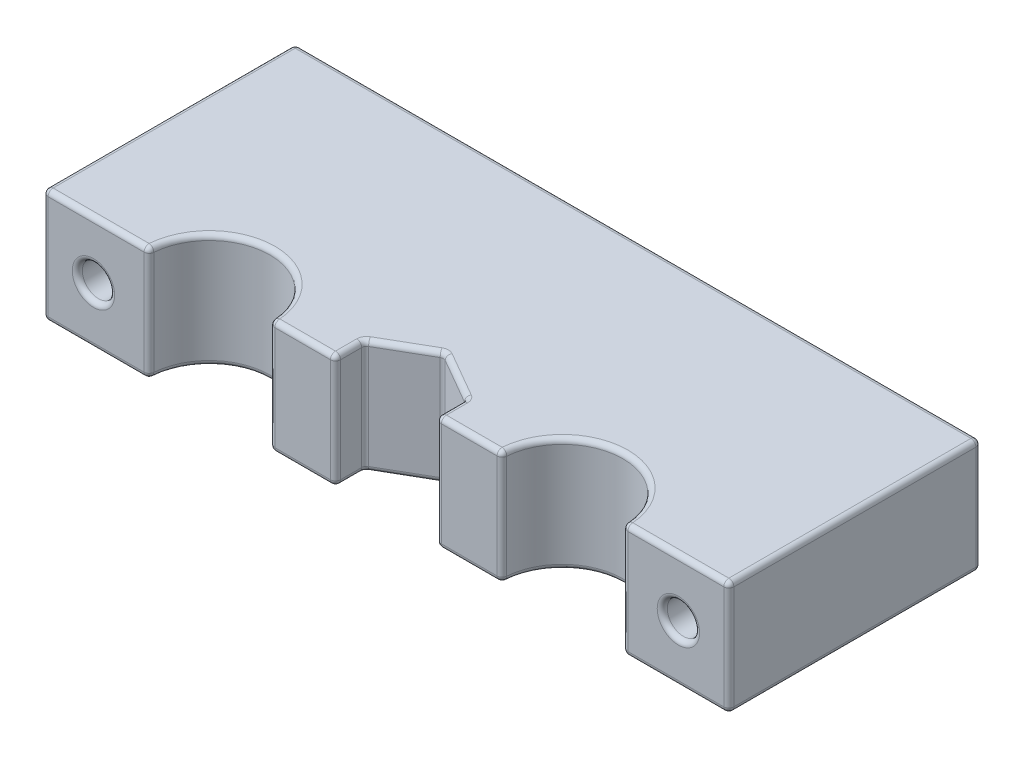
SolidWorks part; units mm, degrees
ref_plane "Front Plane" through (0, 0, 0) normal (0, 0, 1) x (1, 0, 0)
ref_plane "Top Plane" through (0, 0, 0) normal (0, 1, 0) x (1, 0, 0)
ref_plane "Right Plane" through (0, 0, 0) normal (1, 0, 0) x (0, 0, -1)
sketch "Sketch1" plane through (0, 0, 0) normal (0, 1, 0) x (1, 0, 0)
  line L0 (34, 0) -> (34, 25) construction
  line L5 (0, 0) -> (68, 0) construction
  line L6 (0, 0) -> (0, 25) construction
  line L13 (0, 25) -> (68, 25) construction
  line L14 (68, 0) -> (68, 25) construction
  line L15 (57.5, 0) -> (68, 0)
  line L16 (29, 2.8868) -> (29, -2.8868) construction
  line L17 (29, -2.8868) -> (34, -5.7735) construction
  line L18 (34, -5.7735) -> (39, -2.8868) construction
  line L19 (39, -2.8868) -> (39, 2.8868) construction
  line L20 (39, 2.8868) -> (34, 5.7735) construction
  line L21 (34, 5.7735) -> (29, 2.8868) construction
  line L22 (68, 0) -> (68, 25)
  line L23 (68, 25) -> (0, 25)
  line L24 (0, 25) -> (0, 0)
  line L25 (0, 0) -> (10.5, 0)
  line L26 (22.5, 0) -> (29, 0)
  line L27 (29, 0) -> (29, 2.8868)
  line L28 (29, 2.8868) -> (34, 5.7735)
  line L29 (34, 5.7735) -> (39, 2.8868)
  line L30 (39, 2.8868) -> (39, 0)
  line L31 (39, 0) -> (45.5, 0)
  circle A2 centre (16.5, 0) radius 6 construction
  circle A3 centre (34, 0) radius 5 construction
  circle A4 centre (51.5, 0) radius 6 construction
  arc A5 (10.5, 0) -> (22.5, 0) centre (16.5, 0) cw
  arc A6 (45.5, 0) -> (57.5, 0) centre (51.5, 0) cw
  point P7 (34, 0)
  dimension "D3" = 12
  dimension "D4" = 25
  dimension "D1" = 17.5
  dimension "D2" = 68
  dimension "D5" = 10
extrude "Boss-Extrude1" add sketch "Sketch1" along normal blind 11.3
sketch "Sketch2" plane through (0, 0, -25) normal (0, 0, -1) x (-1, 0, 0)
  line L0 (-34, 11.3) -> (-34, 0) construction
  line L1 (-68, 11.3) -> (0, 11.3) construction
  line L2 (-68, 0) -> (0, 0) construction
  line L3 (0, 5.65) -> (-5, 5.65) construction
  line L4 (0, 11.3) -> (0, 0) construction
  circle A0 centre (-5, 5.65) radius 1.6
  circle A1 centre (-63, 5.65) radius 1.6
  dimension "D1" = 3.2
  dimension "D2" = 29
extrude "Cut-Extrude1" cut sketch "Sketch2" against normal through all
fillet "Fillet1" radius 0.5 43 edges at (29, 5.65, 0) (29, 5.65, -2.8868) (34, 5.65, -5.7735) (39, 5.65, -2.8868) (64.6, 5.65, 0) (3.4, 5.65, 0) (10.5, 5.65, 0) (22.5, 5.65, 0) (45.5, 5.65, 0) (57.5, 5.65, 0) (68, 5.65, 0) (0, 5.65, 0) (68, 5.65, -25) (0, 5.65, -25) (64.6, 5.65, -25) (3.4, 5.65, -25) (16.5, 0, -6) (25.75, 0, 0) (29, 0, -1.4434) (31.5, 0, -4.3301) (36.5, 0, -4.3301) (39, 0, -1.4434) (42.25, 0, 0) (51.5, 0, -6) (62.75, 0, 0) (68, 0, -12.5) (34, 0, -25) (0, 0, -12.5) (5.25, 0, 0) (0, 11.3, -12.5) (34, 11.3, -25) (68, 11.3, -12.5) (62.75, 11.3, 0) (51.5, 11.3, -6) (42.25, 11.3, 0) (39, 11.3, -1.4434) (36.5, 11.3, -4.3301) (31.5, 11.3, -4.3301) (29, 11.3, -1.4434) (25.75, 11.3, 0) (16.5, 11.3, -6) (5.25, 11.3, 0) (39, 5.65, 0)
